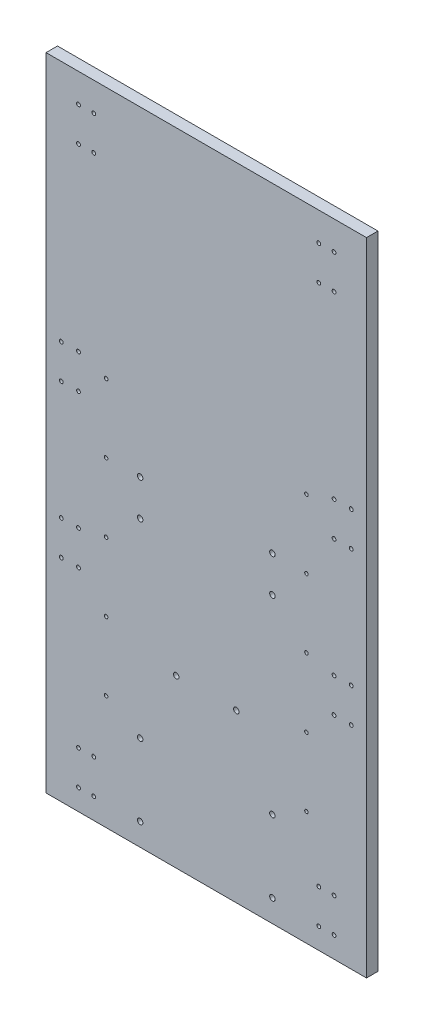
SolidWorks part; units mm, degrees
material "Beech"
ref_plane "Front Plane" through (0, 0, 0) normal (0, 0, 1) x (1, 0, 0)
ref_plane "Top Plane" through (0, 0, 0) normal (0, 1, 0) x (1, 0, 0)
ref_plane "Right Plane" through (0, 0, 0) normal (1, 0, 0) x (0, 0, -1)
sketch "Sketch1" plane through (0, 0, 0) normal (0, 0, 1) x (1, 0, 0)
  line L8 (266.573, 7002.78) -> (-266.573, 7002.78)
  line L9 (-266.573, 7002.78) -> (-266.573, 5935.98)
  line L10 (-266.573, 5935.98) -> (266.573, 5935.98)
  line L11 (266.573, 5935.98) -> (266.573, 7002.78)
  point P2 (0, 7002.78)
  dimension "D1" = 1066.8
  dimension "D2" = 533.146
extrude "Boss-Extrude1" add sketch "Sketch1" against normal blind 19.05
hole_wizard "23/64 (0.35938) Diameter Hole1" positions "Sketch2" profile "Sketch3" hole size "23/64" standard "ANSI Inch" end condition through all
sketch "Sketch2" plane through (0, 0, -19.05) normal (0, 0, -1) x (-1, 0, 0)
  point P15 (110, 5973.262)
  point P18 (110, 6093.262)
  point P21 (-110, 6093.262)
  point P24 (-110, 5973.262)
  point P27 (-50, 6213.262)
  point P30 (50, 6213.262)
  point P33 (-110, 6409.662)
  point P36 (-110, 6469.662)
  point P39 (110, 6409.662)
  point P42 (110, 6469.662)
sketch "Sketch3" plane through (-110, 5973.262, -19.05) normal (1, 0, 0) x (0, 1, 0)
  line L0 (0, 0) -> (0, 19.05)
  line L1 (0, 19.05) -> (4.5641, 19.05)
  line L2 (4.5641, 19.05) -> (4.5641, 0)
  line L5 (4.5641, 0) -> (0, 0)
  line L11 (0, -6.35) -> (0, 107.95) construction
  dimension "Thru Hole Dia." = 9.1283
  dimension "Thru Hole Depth" = 19.05
sketch "Sketch4" plane through (0, 0, 0) normal (0, 0, 1) x (1, 0, 0)
  line L0 (-266.573, 7002.78) -> (-266.573, 5935.98) construction
  line L1 (-266.573, 5935.98) -> (-222.123, 5935.98)
  line L2 (-266.573, 5935.98) -> (-266.573, 6012.18)
  line L3 (-266.573, 6012.18) -> (-222.123, 6012.18)
  line L4 (-222.123, 5935.98) -> (-222.123, 6012.18)
  line L5 (-266.573, 7002.78) -> (-222.123, 7002.78)
  line L6 (-266.573, 7002.78) -> (-266.573, 6926.58)
  line L7 (-266.573, 6926.58) -> (-222.123, 6926.58)
  line L8 (-222.123, 7002.78) -> (-222.123, 6926.58)
  line L9 (266.573, 7002.78) -> (-266.573, 7002.78) construction
  line L10 (266.573, 5935.98) -> (266.573, 7002.78) construction
  line L11 (266.573, 7002.78) -> (222.123, 7002.78)
  line L12 (266.573, 7002.78) -> (266.573, 6926.58)
  line L13 (266.573, 6926.58) -> (222.123, 6926.58)
  line L14 (222.123, 7002.78) -> (222.123, 6926.58)
  line L15 (-266.573, 5935.98) -> (266.573, 5935.98) construction
  line L16 (266.573, 5935.98) -> (222.123, 5935.98)
  line L17 (266.573, 5935.98) -> (266.573, 6012.18)
  line L18 (266.573, 6012.18) -> (222.123, 6012.18)
  line L19 (222.123, 5935.98) -> (222.123, 6012.18)
  dimension "D1" = 76.2
  dimension "D2" = 44.45
split line "Split Line1" [suppressed]
hole_wizard "15/64 (0.23438) Diameter Hole1" positions "Sketch5" profile "Sketch6" hole size "15/64" standard "ANSI Inch" end condition through all
sketch "Sketch5" plane through (0, 0, -19.05) normal (0, 0, -1) x (-1, 0, 0)
  point P0 (166.6875, 6125.8958)
  point P2 (166.6875, 6240.1958)
  point P4 (166.6875, 6354.4958)
  point P6 (166.6875, 6468.7958)
  point P8 (166.6875, 6583.0958)
  point P14 (-166.6875, 6125.8958)
  point P16 (-166.6875, 6240.1958)
  point P18 (-166.6875, 6354.4958)
  point P20 (-166.6875, 6468.7958)
  point P22 (-166.6875, 6583.0958)
sketch "Sketch6" plane through (-166.6875, 6125.8958, -19.05) normal (1, 0, 0) x (0, 1, 0)
  line L0 (0, 0) -> (0, 19.05)
  line L1 (0, 19.05) -> (2.9766, 19.05)
  line L2 (2.9766, 19.05) -> (2.9766, 0)
  line L5 (2.9766, 0) -> (0, 0)
  line L11 (0, -6.35) -> (0, 107.95) construction
  dimension "Thru Hole Dia." = 5.9533
  dimension "Thru Hole Depth" = 19.05
hole_wizard "1/4 (0.25) Diameter Hole1" positions "Sketch9" profile "Sketch10" hole size "1/4" standard "ANSI Inch" end condition through all
sketch "Sketch9" plane through (0, 0, 0) normal (0, 0, 1) x (1, 0, 0)
  line L0 (0, 7002.78) -> (0, 5935.98) construction
  line L1 (-266.573, 5935.98) -> (266.573, 5935.98) construction
  point P0 (-212.598, 6955.155)
  point P2 (-212.598, 6898.005)
  point P4 (-187.198, 6898.005)
  point P6 (-187.198, 6955.155)
  point P12 (-241.173, 6598.9708)
  point P14 (-241.173, 6541.8208)
  point P16 (-212.598, 6541.8208)
  point P18 (-212.598, 6598.9708)
  point P24 (-212.598, 6344.9708)
  point P26 (-241.173, 6344.9708)
  point P28 (-241.173, 6287.8208)
  point P30 (-212.598, 6287.8208)
  point P36 (-212.598, 6028.055)
  point P38 (-187.198, 6028.055)
  point P40 (-187.198, 5970.905)
  point P42 (-212.598, 5970.905)
  point P55 (212.598, 5970.905)
  point P56 (187.198, 5970.905)
  point P57 (187.198, 6028.055)
  point P58 (212.598, 6028.055)
  point P59 (212.598, 6287.8208)
  point P60 (241.173, 6287.8208)
  point P61 (241.173, 6344.9708)
  point P62 (212.598, 6344.9708)
  point P63 (212.598, 6598.9708)
  point P64 (212.598, 6541.8208)
  point P65 (241.173, 6541.8208)
  point P66 (241.173, 6598.9708)
  point P67 (187.198, 6955.155)
  point P68 (187.198, 6898.005)
  point P69 (212.598, 6898.005)
  point P70 (212.598, 6955.155)
sketch "Sketch10" plane through (-212.598, 6955.155, 0) normal (1, 0, 0) x (0, -1, 0)
  line L0 (0, 0) -> (0, 19.05)
  line L1 (0, 19.05) -> (3.175, 19.05)
  line L2 (3.175, 19.05) -> (3.175, 0)
  line L5 (3.175, 0) -> (0, 0)
  line L11 (0, -6.35) -> (0, 107.95) construction
  dimension "Thru Hole Dia." = 6.35
  dimension "Thru Hole Depth" = 19.05
